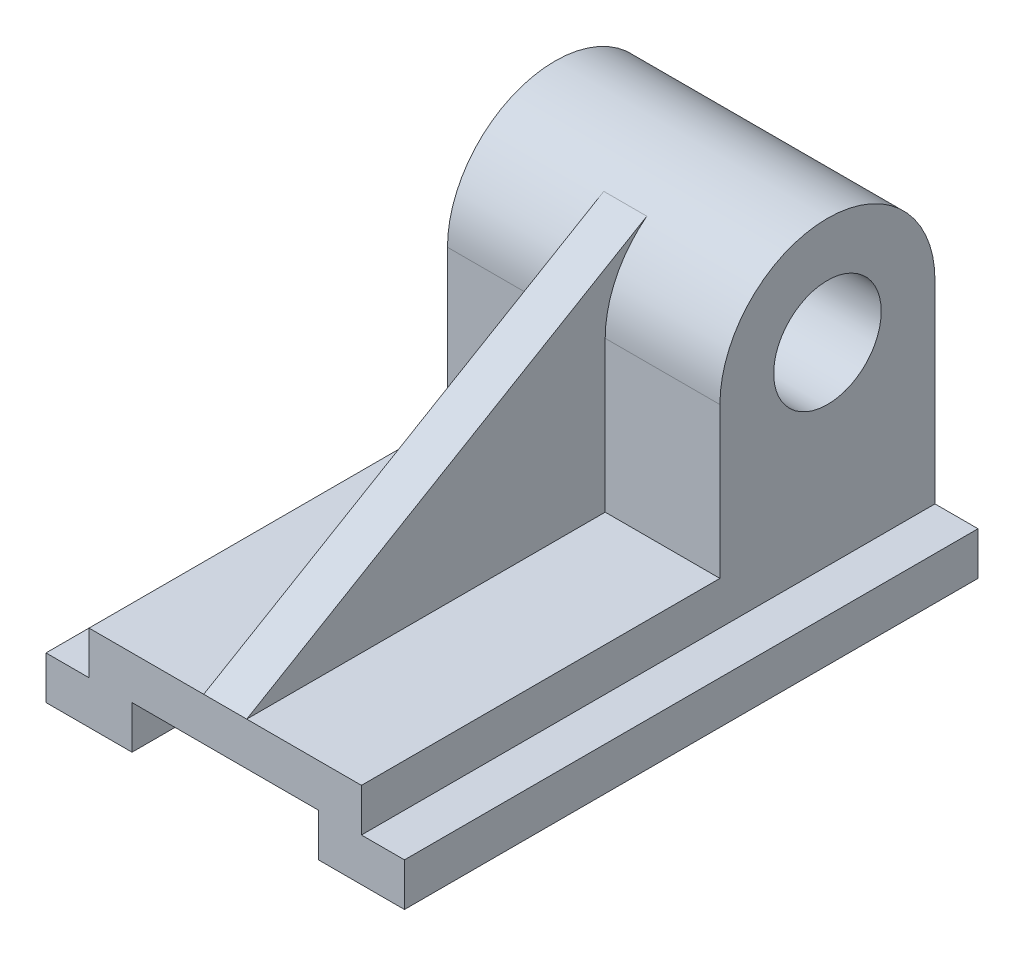
SolidWorks part; units mm, degrees
ref_plane "Front Plane" through (0, 0, 0) normal (0, 0, 1) x (1, 0, 0)
ref_plane "Top Plane" through (0, 0, 0) normal (0, 1, 0) x (1, 0, 0)
ref_plane "Right Plane" through (0, 0, 0) normal (1, 0, 0) x (0, 0, -1)
sketch "Sketch1" plane through (0, 0, 0) normal (0, 0, 1) x (1, 0, 0)
  line L0 (-380, 60) -> (380, 60)
  line L1 (500, 60) -> (-500, 60)
  line L2 (500, 60) -> (500, -60)
  line L3 (500, -60) -> (-500, -60)
  line L4 (-500, 60) -> (-500, -60)
  line L5 (500, 60) -> (-500, -60) construction
  line L6 (500, -60) -> (-500, 60) construction
  line L11 (-380, 60) -> (-380, 180)
  line L12 (-380, 180) -> (380, 180)
  line L13 (380, 180) -> (380, 60)
  line L14 (-500, -60) -> (-260, -60)
  line L15 (-260, -60) -> (-260, 60)
  line L16 (-260, 60) -> (260, 60)
  line L17 (260, 60) -> (260, -60)
  line L18 (260, -60) -> (-260, -60)
  point P0 (0, 0)
  point P5 (1.4161, 138.2302)
  dimension "D1" = 120
  dimension "D2" = 1000
extrude "Boss-Extrude1" add sketch "Sketch1" against normal mid plane 1600 contours L0 L17 L3 L2 L1 | L13 L12 L11 L0 L1 | L3 L15 L0 L1 L4
sketch "Sketch2" plane through (380, 0, 0) normal (1, 0, 0) x (0, 0, -1)
  line L0 (800, 180) -> (800, 600)
  line L1 (200, 600) -> (200, 180)
  line L2 (800, 180) -> (-800, 180) construction
  line L3 (200, 180) -> (800, 180)
  arc A0 (800, 600) -> (200, 600) centre (500, 600) ccw
  circle A1 centre (500, 600) radius 150
extrude "Boss-Extrude5" add sketch "Sketch2" against normal up to surface (760 mm away) up to face at (-380, 120, 0)
sketch "Sketch4" plane through (0, 0, 0) normal (1, 0, 0) x (0, 0, -1)
  line L0 (-800, 180) -> (316.095, 837.021)
  arc A0 (800, 600) -> (200, 600) centre (500, 600) ccw construction
rib "Rib1" sketch "Sketch4" sketch "Sketch4" thickness 120 extrusion direction parallel to sketch draft on no parameters "D1"=120
